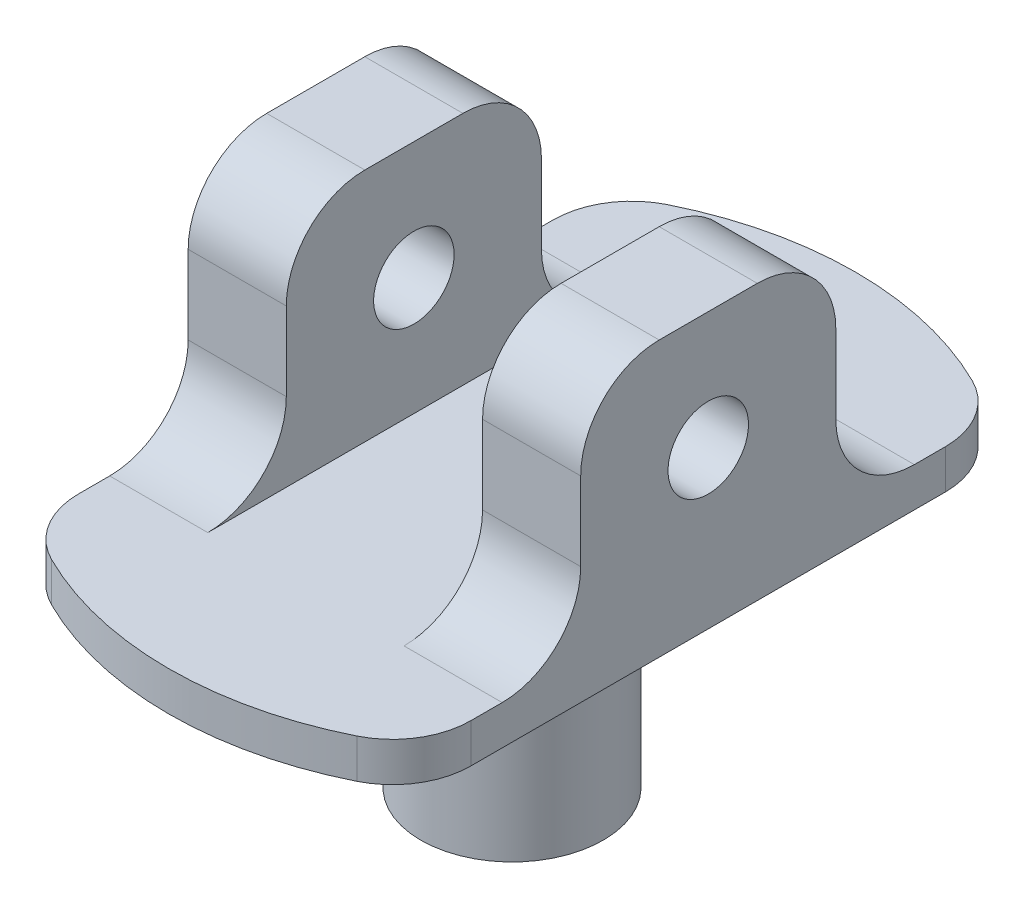
SolidWorks part; units mm, degrees
ref_plane "Front Plane" through (0, 0, 0) normal (0, 0, 1) x (1, 0, 0)
ref_plane "Top Plane" through (0, 0, 0) normal (0, 1, 0) x (1, 0, 0)
ref_plane "Right Plane" through (0, 0, 0) normal (1, 0, 0) x (0, 0, -1)
sketch "Sketch1" plane through (0, 0, 0) normal (0, 1, 0) x (1, 0, 0)
  circle A0 centre (0, 0) radius 4.65
  dimension "D1" = 9.3
extrude "Boss-Extrude1" add sketch "Sketch1" along normal blind 12
sketch "Sketch2" plane through (0, 12, 0) normal (0, 1, 0) x (1, 0, 0)
  circle A0 centre (0, 0) radius 17.5
  dimension "D1" = 35
extrude "Boss-Extrude2" add sketch "Sketch2" along normal blind 2
sketch "Sketch3" plane through (0, 14, 0) normal (0, 1, 0) x (1, 0, 0)
  line L0 (0, 0) -> (0, 17.5) construction
  line L2 (5, 6.5) -> (10, 6.5)
  line L3 (5, 6.5) -> (5, -6.5)
  line L4 (5, -6.5) -> (10, -6.5)
  line L5 (10, 6.5) -> (10, -6.5)
  circle A0 centre (0, 0) radius 17.5 construction
  point P9 (5, 0)
  dimension "D1" = 5
  dimension "D2" = 13
  dimension "D3" = 5
extrude "Boss-Extrude3" add sketch "Sketch3" along normal blind 12 contours L2 L5 L4 L3
mirror "Mirror1" about plane through (0, 0, 0) normal (1, 0, 0) of "Boss-Extrude3"
fillet "Fillet1" radius 4 4 edges at (-7.5, 26, -6.5) (7.5, 26, -6.5) (7.5, 26, 6.5) (-7.5, 26, 6.5)
fillet "Fillet2" radius 4 4 edges at (7.5, 14, -6.5) (-7.5, 14, -6.5) (-7.5, 14, 6.5) (7.5, 14, 6.5)
sketch "Sketch4" plane through (0, 14, 0) normal (0, 1, 0) x (1, 0, 0)
  line L0 (10, 0) -> (10, 14.3614)
  line L1 (10, 2.5) -> (10, -2.5) construction
  line L2 (10, 14.3614) -> (24.3824, 14.3614)
  line L3 (24.3824, 14.3614) -> (24.3824, -16.5205)
  line L4 (24.3824, -16.5205) -> (10, -16.5205)
  line L5 (10, -16.5205) -> (10, 0)
  circle A1 centre (0, 0) radius 17.5
  circle A2 centre (0, 0) radius 17.5
  circle M6 centre (0, 0) radius 17.5
  line M8 (10, 10.5) -> (10, -10.5)
  dimension "D1" = 0
extrude "Cut-Extrude1" cut sketch "Sketch4" against normal through all contours L5 L0 M6 M8
mirror "Mirror2" about plane through (0, 0, 0) normal (1, 0, 0) of "Cut-Extrude1"
sketch "Sketch5" plane through (10, 0, 0) normal (1, 0, 0) x (0, 0, -1)
  line L0 (-6.5, 22) -> (-6.5, 18) construction
  line L1 (2.5, 26) -> (-2.5, 26) construction
  circle A0 centre (0, 20) radius 2.05
  point P4 (-6.5, 20)
  point P7 (0, 26)
  dimension "D1" = 4.1
extrude "Cut-Extrude2" cut sketch "Sketch5" against normal blind 70
fillet "Fillet3" radius 4 4 edges at (10, 13, 14.3614) (10, 13, -14.3614) (-10, 13, -14.3614) (-10, 13, 14.3614)
